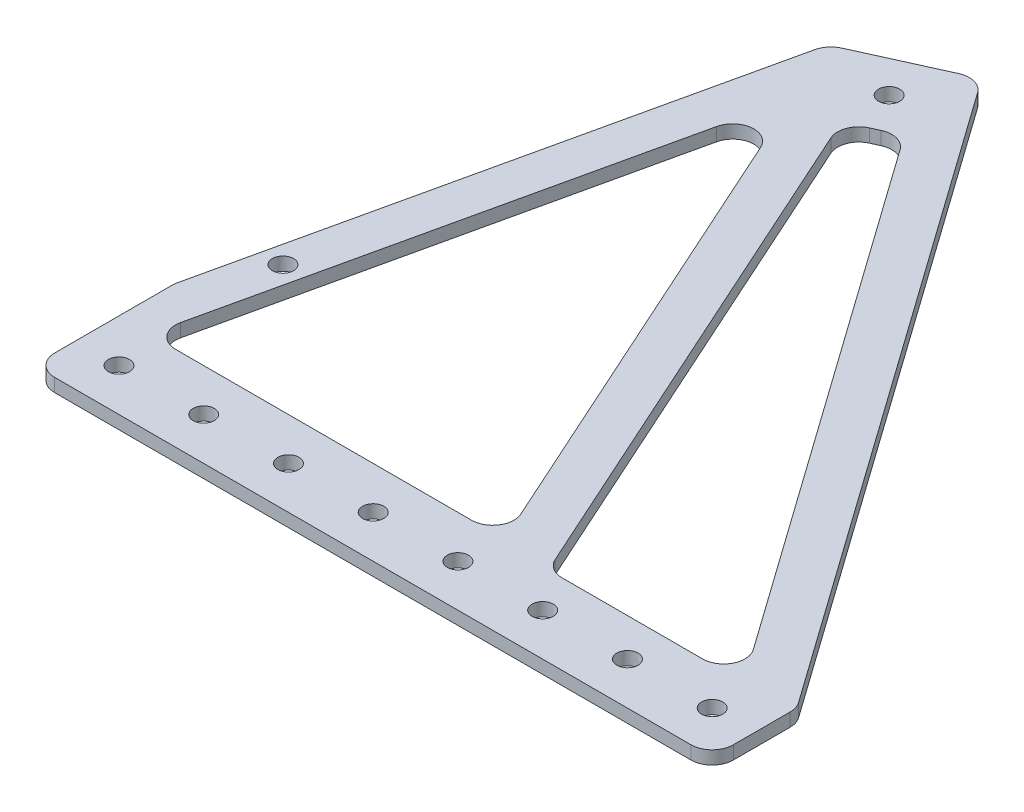
SolidWorks part; units mm, degrees
ref_plane "Front Plane" through (0, 0, 0) normal (0, 0, 1) x (1, 0, 0)
ref_plane "Top Plane" through (0, 0, 0) normal (0, 1, 0) x (1, 0, 0)
ref_plane "Right Plane" through (0, 0, 0) normal (1, 0, 0) x (0, 0, -1)
sketch "Sketch1" plane through (0, 0, 0) normal (0, 1, 0) x (1, 0, 0)
  line L0 (-16, 0) -> (16, 0) construction
  line L1 (-31.2294, 8) -> (-76.046, 107.188)
  line L2 (-24, -8) -> (24, -8)
  line L5 (24, -8) -> (24, 8)
  line L6 (0, 8) -> (0, -8) construction
  line L7 (-24, 0) -> (24, 0) construction
  line L8 (-81.5242, 119.3123) -> (-61.4758, 128.3709)
  line L9 (-61.4758, 128.3709) -> (24, 8)
  line L10 (-67.5, 116.9134) -> (0, 0) construction
  line L11 (-67.5, 116.9134) -> (-71.5, 123.8416) construction
  line L12 (-63.4802, 109.951) -> (-59.4883, 111.7547)
  line L13 (24, -8) -> (-24, -8) construction
  line L14 (24, -8) -> (24, 8) construction
  line L15 (24, 8) -> (-24, 8) construction
  line L16 (-24, -8) -> (-24, 8) construction
  line L17 (0, 8) -> (0, -8) construction
  line L18 (24, 0) -> (-24, 0) construction
  line L19 (-63.4802, 109.951) -> (-67.662, 108.0615)
  line L20 (-67.662, 108.0615) -> (-22.058, 7.1309)
  line L21 (-22.058, 7.1309) -> (14.8053, 7.1309)
  line L22 (14.8053, 7.1309) -> (-59.4883, 111.7547)
  line L23 (-81.5242, 119.3123) -> (-104.1269, 18.5896)
  line L24 (-104.1269, -8) -> (-86.0937, -8)
  line L25 (-98.3042, 8) -> (-76.046, 107.188)
  line L26 (-98.3042, 8) -> (-31.2294, 8)
  line L27 (-86.0937, -8) -> (-24, -8)
  line L28 (-104.1269, -8) -> (-104.1269, 18.5896)
  line L29 (-96, 0) -> (-97.0217, 31.9837) construction
  circle A0 centre (-16, 0) radius 2
  circle A1 centre (16, 0) radius 2
  circle A2 centre (0, 0) radius 2
  circle A3 centre (-67.5, 116.9134) radius 2
  circle A4 centre (-32, 0) radius 2
  circle A5 centre (-48, 0) radius 2
  circle A6 centre (-64, 0) radius 2
  circle A7 centre (-80, 0) radius 2
  circle A8 centre (-96, 0) radius 2
  circle A11 centre (-97.0217, 31.9837) radius 2
  point P3 (-71.5, 123.8416)
  point P4 (0, 0)
  point P7 (0, 0)
  point P20 (-63.4802, 109.951)
  point P23 (-3.6263, 7.1309)
  point P43 (0, 0)
  point P44 (-98.3042, 31.9171)
  dimension "D2" = 4
  dimension "D15" = 4
  dimension "D1" = 32
  dimension "D3" = 60
  dimension "D4" = 8
  dimension "D5" = 22
  dimension "D6" = 8
  dimension "D7" = 135
  dimension "D8" = 143
  dimension "D9" = 8
  dimension "D10" = 8
  dimension "D12" = 32
  dimension "D13" = 12
  dimension "D14" = 8
  dimension "D16" = 4
  dimension "D11" = 6
extrude "Boss-Extrude1" add sketch "Sketch1" along normal blind 2.5
fillet "Fillet2" radius 4 13 edges at (-67.662, 1.25, -108.0615) (-59.4883, 1.25, -111.7547) (-22.058, 1.25, -7.1309) (24, 1.25, 8) (24, 1.25, -8) (14.8053, 1.25, -7.1309) (-61.4758, 1.25, -128.3709) (-76.046, 1.25, -107.188) (-81.5242, 1.25, -119.3123) (-31.2294, 1.25, -8) (-98.3042, 1.25, -8) (-104.1269, 1.25, 8) (-104.1269, 1.25, -18.5896)
